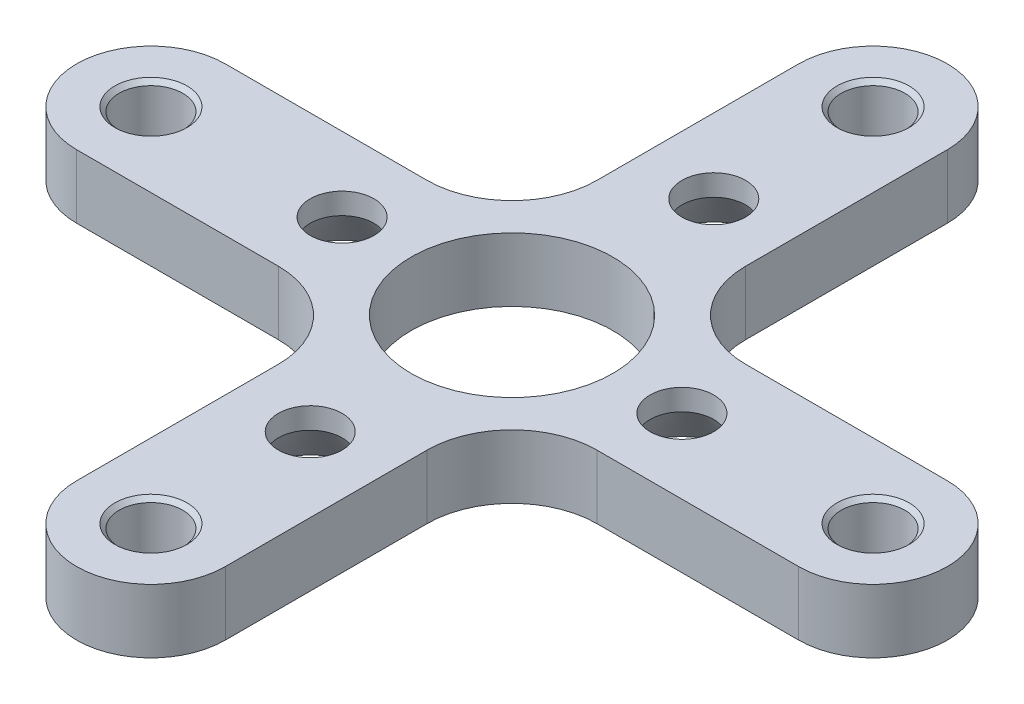
SolidWorks part; units mm, degrees
ref_plane "Front Plane" through (0, 0, 0) normal (0, 0, 1) x (1, 0, 0)
ref_plane "Top Plane" through (0, 0, 0) normal (0, 1, 0) x (1, 0, 0)
ref_plane "Right Plane" through (0, 0, 0) normal (1, 0, 0) x (0, 0, -1)
sketch "Sketch1" plane through (0, 0, 0) normal (0, 1, 0) x (1, 0, 0)
  line L0 (0, 30) -> (0, 0) construction
  line L1 (0, 0) -> (40, 0) construction
  line L2 (-3.5, 7.5) -> (-3.5, 17)
  line L3 (3.5, 7.5) -> (3.5, 17)
  line L4 (7.5, 3.5) -> (17, 3.5)
  line L5 (7.5, -3.5) -> (17, -3.5)
  line L6 (3.5, -7.5) -> (3.5, -17)
  line L7 (-3.5, -7.5) -> (-3.5, -17)
  line L8 (-7.5, -3.5) -> (-17, -3.5)
  line L9 (-7.5, 3.5) -> (-17, 3.5)
  circle A0 centre (0, 17) radius 1.5
  arc A1 (3.5, 17) -> (-3.5, 17) centre (0, 17) ccw
  circle A2 centre (0, 0) radius 4.75
  arc A3 (17, -3.5) -> (17, 3.5) centre (17, 0) ccw
  circle A4 centre (17, 0) radius 1.5
  arc A5 (-3.5, -17) -> (3.5, -17) centre (0, -17) ccw
  circle A6 centre (0, -17) radius 1.5
  arc A7 (-17, 3.5) -> (-17, -3.5) centre (-17, 0) ccw
  circle A8 centre (-17, 0) radius 1.5
  arc A9 (-7.5, -3.5) -> (-3.5, -7.5) centre (-7.5, -7.5) cw
  arc A10 (3.5, -7.5) -> (7.5, -3.5) centre (7.5, -7.5) cw
  arc A11 (7.5, 3.5) -> (3.5, 7.5) centre (7.5, 7.5) cw
  arc A12 (-3.5, 7.5) -> (-7.5, 3.5) centre (-7.5, 7.5) cw
  circle A13 centre (0, 9.5) radius 1.5
  circle A14 centre (8, 0) radius 1.5
  circle A15 centre (-8, 0) radius 1.5
  circle A16 centre (0, -9.5) radius 1.5
  point P32 (0, 0)
  dimension "D1" = 7
  dimension "D2" = 3
  dimension "D4" = 9.5
  dimension "D6" = 4
  dimension "D7" = 3
  dimension "D3" = 17
  dimension "D8" = 9.5
  dimension "D9" = 8
  dimension "D5" = 4
extrude "Boss-Extrude1" add sketch "Sketch1" along normal blind 3
chamfer "Chamfer1" distance 0.2 angle 45 8 edges at (0, 0, 18.5) (0, 3, 18.5) (17, 0, 1.5) (17, 3, 1.5) (0, 0, -15.5) (0, 3, -15.5) (-17, 0, 1.5) (-17, 3, 1.5)
chamfer "Chamfer2" distance 2 angle 35 4 edges at (0, 0, -8) (8, 0, 1.5) (0, 0, 8) (-8, 0, -1.5)
